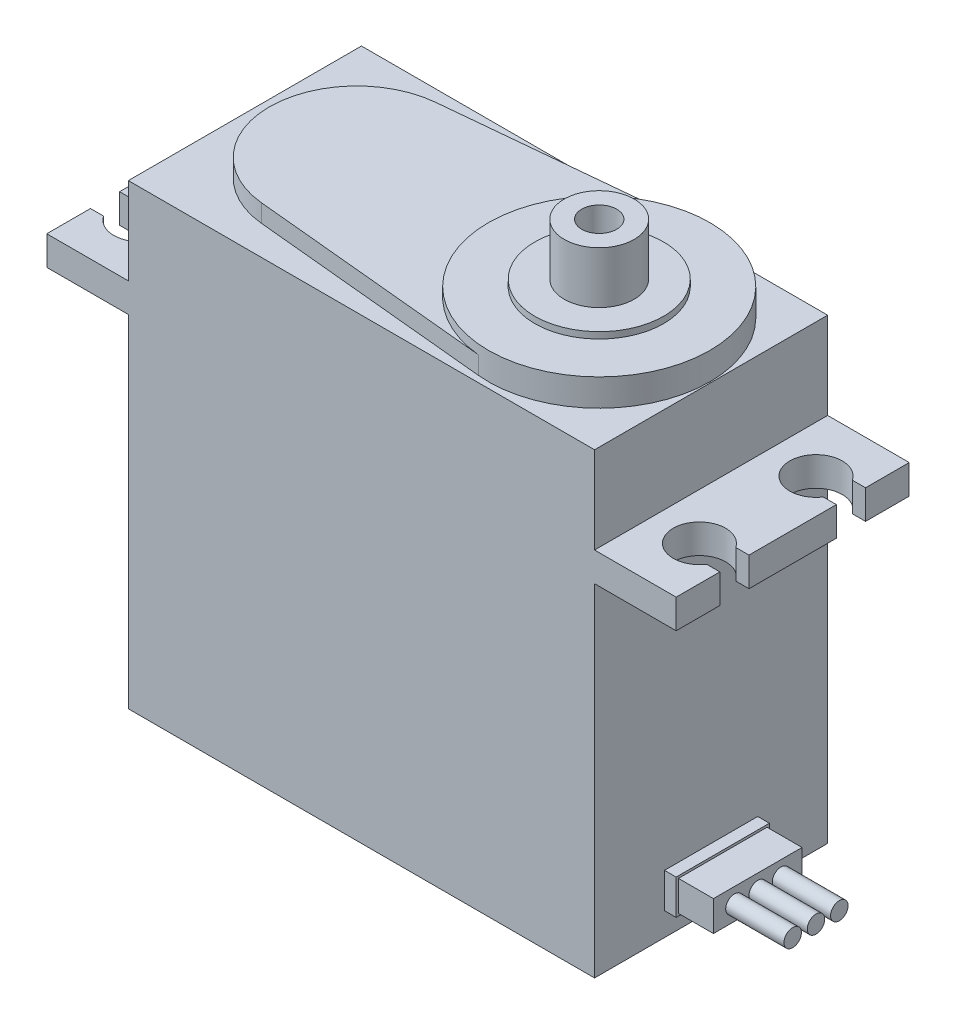
SolidWorks part; units mm, degrees
ref_plane "정면" through (0, 0, 0) normal (0, 0, 1) x (1, 0, 0)
ref_plane "윗면" through (0, 0, 0) normal (0, 1, 0) x (1, 0, 0)
ref_plane "우측면" through (0, 0, 0) normal (1, 0, 0) x (0, 0, -1)
sketch "스케치1" plane through (0, 0, 0) normal (0, 1, 0) x (1, 0, 0)
  line L1 (-20, 10) -> (20, 10)
  line L2 (-20, 10) -> (-20, -10)
  line L3 (-20, -10) -> (20, -10)
  line L4 (20, 10) -> (20, -10)
  line L5 (-20, 10) -> (20, -10) construction
  line L6 (-20, -10) -> (20, 10) construction
  point P0 (0, 0)
  dimension "D1" = 40
  dimension "D2" = 20
extrude "보스-돌출1" add sketch "스케치1" along normal blind 29.3
sketch "스케치2" plane through (0, 29.3, 0) normal (0, 1, 0) x (1, 0, 0)
  line L0 (-24, 10) -> (-24, -10) construction
  line L1 (-27, 10) -> (27, 10)
  line L2 (-27, 10) -> (-27, 6.25)
  line L3 (-27, -10) -> (27, -10)
  line L4 (27, 10) -> (27, 6.25)
  line L5 (-27, 10) -> (27, -10) construction
  line L6 (-27, -10) -> (27, 10) construction
  line L7 (24, 10) -> (24, -10) construction
  line L8 (-27, 3.75) -> (-27, -3.75)
  line L9 (-25.8708, 3.75) -> (-27, 3.75)
  line L11 (-25.8708, 6.25) -> (-27, 6.25)
  line L13 (-27, -6.25) -> (-27, -10)
  line L14 (-25.8708, -6.25) -> (-27, -6.25)
  line L15 (-27, 10) -> (-27, -10) construction
  line L17 (-25.8708, -3.75) -> (-27, -3.75)
  line L19 (27, 3.75) -> (27, -3.75)
  line L20 (25.8686, 3.75) -> (27, 3.75)
  line L22 (25.8686, 6.25) -> (27, 6.25)
  line L24 (27, -6.25) -> (27, -10)
  line L26 (25.8662, -6.25) -> (27, -6.25)
  line L28 (25.8662, -3.75) -> (27, -3.75)
  line L32 (27, 10) -> (27, -10) construction
  arc A0 (-25.8708, 3.75) -> (-25.8708, 6.25) centre (-24, 5) ccw
  arc A1 (-25.8708, -6.25) -> (-25.8708, -3.75) centre (-24, -5) ccw
  arc A2 (25.8662, -3.75) -> (25.8662, -6.25) centre (24, -5) ccw
  arc A3 (25.8686, 6.25) -> (25.8686, 3.75) centre (24, 5) ccw
  point P0 (0, 0)
  dimension "D4" = 5
  dimension "D5" = 5
  dimension "D6" = 4.5
  dimension "D7" = 4.5
  dimension "D9" = 5
  dimension "D10" = 5
  dimension "D12" = 20
  dimension "D1" = 54
  dimension "D13" = 2.5
  dimension "D14" = 1.25
  dimension "D2" = 3
  dimension "D3" = 3
extrude "보스-돌출2" add sketch "스케치2" along normal blind 2.5
sketch "스케치3" plane through (0, 31.8, 0) normal (0, 1, 0) x (1, 0, 0)
  line L0 (27, 10) -> (-27, 10) construction
  line L1 (-20, -10) -> (20, -10)
  line L2 (-20, -10) -> (-20, 10)
  line L3 (-20, 10) -> (20, 10)
  line L4 (20, -10) -> (20, 10)
  line L5 (-20, -10) -> (20, 10) construction
  line L6 (-20, 10) -> (20, -10) construction
  point P0 (0, 0)
  dimension "D1" = 40
extrude "보스-돌출3" add sketch "스케치3" along normal blind 7.45
sketch "스케치4" plane through (0, 39.25, 0) normal (0, 1, 0) x (1, 0, 0)
  line L0 (20, -10) -> (20, 10) construction
  line L1 (-20, 10) -> (-20, -10) construction
  line L4 (-11.1059, 7.4667) -> (9.4866, 9.456)
  line L5 (-11.106, -7.4667) -> (9.4865, -9.456)
  arc A0 (9.4865, -9.456) -> (9.4866, 9.456) centre (10.4, 0) ccw
  arc A1 (-11.1059, 7.4667) -> (-11.106, -7.4667) centre (-10.4, 0) ccw
  dimension "D1" = 19
  dimension "D2" = 9.6
  dimension "D3" = 9.6
  dimension "D4" = 15
extrude "보스-돌출4" add sketch "스케치4" along normal blind 1.53
sketch "스케치5" plane through (0, 40.78, 0) normal (0, 1, 0) x (1, 0, 0)
  circle A0 centre (10.4, 0) radius 9.5
extrude "보스-돌출5" add sketch "스케치5" along normal blind 0.8
sketch "스케치6" plane through (0, 41.58, 0) normal (0, 1, 0) x (1, 0, 0)
  circle A0 centre (10.4, 0) radius 3
  dimension "D1" = 6
extrude "보스-돌출6" add sketch "스케치6" along normal blind 5
sketch "스케치7" plane through (20, 0, 0) normal (1, 0, 0) x (0, 0, -1)
  line L0 (0, 0) -> (0, 6.5576) construction
  line L3 (-4, 5) -> (4, 5)
  line L4 (-4, 5) -> (-4, 2)
  line L5 (-4, 2) -> (4, 2)
  line L6 (4, 5) -> (4, 2)
  line L7 (-4, 5) -> (4, 2) construction
  line L8 (-4, 2) -> (4, 5) construction
  line L9 (-10, 0) -> (10, 0) construction
  point P0 (0, 3.5)
  dimension "D1" = 8
  dimension "D2" = 3
  dimension "D3" = 2
extrude "보스-돌출7" add sketch "스케치7" along normal blind 1
sketch "스케치8" plane through (21, 0, 0) normal (1, 0, 0) x (0, 0, -1)
  line L0 (-4, 5) -> (-4, 2) construction
  line L1 (-3.8, 4.8) -> (3.8, 4.8)
  line L2 (-3.8, 4.8) -> (-3.8, 2.2)
  line L3 (-3.8, 2.2) -> (3.8, 2.2)
  line L4 (3.8, 4.8) -> (3.8, 2.2)
  line L5 (-3.8, 4.8) -> (3.8, 2.2) construction
  line L6 (-3.8, 2.2) -> (3.8, 4.8) construction
  line L7 (4, 5) -> (-4, 5) construction
  line L8 (4, 2) -> (4, 5) construction
  line L9 (-4, 2) -> (4, 2) construction
  point P0 (0, 3.5)
  point P7 (-4, 3.5)
  dimension "D1" = 0.2
  dimension "D2" = 0.2
  dimension "D3" = 0.2
  dimension "D4" = 0.2
extrude "보스-돌출8" add sketch "스케치8" along normal blind 3
sketch "스케치9" plane through (24, 0, 0) normal (1, 0, 0) x (0, 0, -1)
  line L0 (0, 0) -> (0, 6.201) construction
  circle A0 centre (0, 3.5051) radius 0.75
  circle A1 centre (-2, 3.4994) radius 0.75
  circle A2 centre (2, 3.5005) radius 0.75
  dimension "D1" = 1.5
  dimension "D2" = 2
  dimension "D3" = 2
extrude "보스-돌출9" add sketch "스케치9" along normal blind 5
sketch "스케치10" plane through (0, 46.58, 0) normal (0, 1, 0) x (1, 0, 0)
  circle A0 centre (10.4, 0) radius 1.5
  dimension "D1" = 3
extrude "컷-돌출1" cut sketch "스케치10" against normal blind 3
sketch "스케치11" plane through (0, 41.58, 0) normal (0, 1, 0) x (1, 0, 0)
  circle A0 centre (10.4, 0) radius 5.525
  dimension "D1" = 11.05
extrude "보스-돌출11" add sketch "스케치11" along normal blind 0.55
